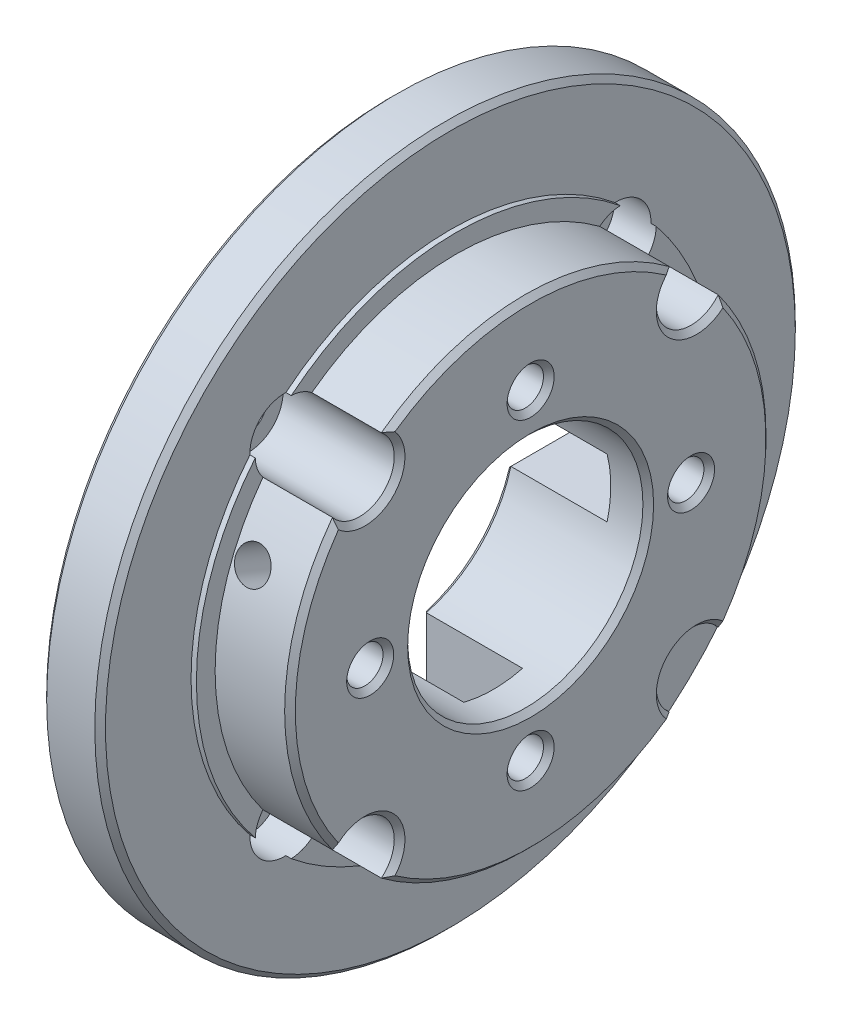
SolidWorks part; units mm, degrees
ref_plane "Ebene vorne" through (0, 0, 0) normal (0, 0, 1) x (1, 0, 0)
ref_plane "Ebene oben" through (0, 0, 0) normal (0, 1, 0) x (1, 0, 0)
ref_plane "Ebene rechts" through (0, 0, 0) normal (1, 0, 0) x (0, 0, -1)
sketch "Sketch1" plane through (0, 0, 0) normal (0, 0, 1) x (1, 0, 0)
  line L0 (0, 0) -> (49.3212, 0) construction
  line L1 (0, 0) -> (0, 32.75)
  line L2 (0, 32.75) -> (5.5, 32.75)
  line L3 (5.5, 32.75) -> (5.5, 24.25)
  line L4 (5.5, 24.25) -> (6, 24.25)
  line L5 (6, 24.25) -> (6, 22.5)
  line L6 (6, 22.5) -> (13, 22.5)
  line L7 (13, 22.5) -> (13, 0)
  line L8 (13, 11) -> (0, 11)
  dimension "D1" = 65.5
  dimension "D2" = 48.5
  dimension "D3" = 45
  dimension "D4" = 0.5
  dimension "D5" = 5.5
  dimension "D6" = 7
  dimension "D7" = 22
revolve "Revolve1" add sketch "Sketch1" angle 360 about L0
hole_wizard "M3 Clearance Hole1" positions "Sketch3" profile "Sketch5" hole size "M3" standard "DIN" end condition through all
sketch "Sketch3" plane through (13, 0, 0) normal (1, 0, 0) x (0, 0, -1)
  line L0 (0, 0) -> (0, 15) construction
  line L2 (0, 0) -> (15, 0) construction
  circle A0 centre (0, 0) radius 15
  point P4 (15, 0)
  point P29 (0, -15)
  point P30 (-15, 0)
  point P31 (0, 15)
  dimension "D1" = 30
  dimension "D2" = 90
  dimension "D3" = 4
sketch "Sketch5" plane through (13, 15, 0) normal (0, 1, 0) x (0, 0, -1)
  line L0 (0, 0) -> (0, 13)
  line L1 (0, 13) -> (1.7, 13)
  line L2 (1.7, 13) -> (1.7, 0)
  line L5 (1.7, 0) -> (0, 0)
  line L11 (0, -6.35) -> (0, 107.95) construction
  dimension "Thru Hole Dia." = 3.4
  dimension "Thru Hole Depth" = 13
sketch "Sketch6" plane through (0, 0, 0) normal (-1, 0, 0) x (0, 0, 1)
  line L0 (-2.75, 13.4123) -> (-2.75, 10.6507)
  line L7 (0, 11.8246) -> (2.75, 13.4123)
  line L8 (2.75, 13.4123) -> (2.75, 16.5877)
  line L15 (2.75, 16.5877) -> (0, 18.1754)
  line L16 (0, 18.1754) -> (-2.75, 16.5877)
  line L23 (-2.75, 16.5877) -> (-2.75, 13.4123)
  line L24 (-2.75, 13.4123) -> (0, 11.8246)
  line L31 (2.75, 13.4123) -> (2.75, 10.6507)
  line L32 (11.8246, 0) -> (13.4123, -2.75)
  line L33 (13.4123, -2.75) -> (16.5877, -2.75)
  line L34 (16.5877, -2.75) -> (18.1754, 0)
  line L35 (18.1754, 0) -> (16.5877, 2.75)
  line L36 (16.5877, 2.75) -> (13.4123, 2.75)
  line L37 (13.4123, 2.75) -> (11.8246, 0)
  line L38 (13.4123, 2.75) -> (10.6507, 2.75)
  line L39 (13.4123, -2.75) -> (10.6507, -2.75)
  line L40 (0, -11.8246) -> (-2.75, -13.4123)
  line L41 (-2.75, -13.4123) -> (-2.75, -16.5877)
  line L42 (-2.75, -16.5877) -> (0, -18.1754)
  line L43 (0, -18.1754) -> (2.75, -16.5877)
  line L44 (2.75, -16.5877) -> (2.75, -13.4123)
  line L45 (2.75, -13.4123) -> (0, -11.8246)
  line L46 (2.75, -13.4123) -> (2.75, -10.6507)
  line L47 (-2.75, -13.4123) -> (-2.75, -10.6507)
  line L48 (-11.8246, 0) -> (-13.4123, 2.75)
  line L49 (-13.4123, 2.75) -> (-16.5877, 2.75)
  line L50 (-16.5877, 2.75) -> (-18.1754, 0)
  line L51 (-18.1754, 0) -> (-16.5877, -2.75)
  line L52 (-16.5877, -2.75) -> (-13.4123, -2.75)
  line L53 (-13.4123, -2.75) -> (-11.8246, 0)
  line L54 (-13.4123, -2.75) -> (-10.6507, -2.75)
  line L55 (-13.4123, 2.75) -> (-10.6507, 2.75)
  circle A0 centre (0, 15) radius 2.75 construction
  circle A3 centre (0, 0) radius 11 construction
  point P41 (0, 0)
  dimension "D1" = 5.5
extrude "Cut-Extrude1" cut sketch "Sketch6" against normal offset from surface (9.5 mm away) 3.5
sketch "Sketch7" plane through (13, 0, 0) normal (1, 0, 0) x (0, 0, -1)
  line L1 (-15.5, -15.5) -> (15.5, -15.5)
  line L2 (-15.5, -15.5) -> (-15.5, 15.5)
  line L3 (-15.5, 15.5) -> (15.5, 15.5)
  line L4 (15.5, -15.5) -> (15.5, 15.5)
  line L5 (-15.5, -15.5) -> (15.5, 15.5) construction
  line L6 (-15.5, 15.5) -> (15.5, -15.5) construction
  circle A0 centre (0, 0) radius 21.9203
  circle A1 centre (-15.5, 15.5) radius 3.25
  circle A2 centre (-15.5, -15.5) radius 3.25
  circle A3 centre (15.5, -15.5) radius 3.25
  circle A4 centre (15.5, 15.5) radius 3.25
  dimension "D1" = 31
  dimension "D3" = 6.5
  dimension "D2" = 31
  dimension "D4" = 4
extrude "Cut-Extrude2" cut sketch "Sketch7" against normal up to surface (7.5 mm away) contours A1 | A4 | A3 | A2 up to face at (5.5, 0, 24.25)
hole_wizard "CBORE for M3 Hex Socket Head Cap Screw1" positions "Sketch8" profile "Sketch9" counterbore size "M3" standard "DIN" end condition through all
sketch "Sketch8" plane through (5.5, 0, 0) normal (1, 0, 0) x (0, 0, -1)
  point P0 (-15.5, 15.5)
  point P3 (15.5, 15.5)
  point P6 (15.5, -15.5)
  point P9 (-15.5, -15.5)
sketch "Sketch9" plane through (5.5, 15.5, 15.5) normal (0, 1, 0) x (0, 0, -1)
  line L0 (0, 0) -> (0, 5.5)
  line L1 (0, 5.5) -> (1.7, 5.5)
  line L3 (1.7, 5.5) -> (1.7, 3.4)
  line L4 (1.7, 3.4) -> (3.25, 3.4)
  line L5 (3.25, 3.4) -> (3.25, 0)
  line L7 (3.25, 0) -> (0, 0)
  line L11 (0, -6.35) -> (0, 107.95) construction
  dimension "Thru Hole Dia." = 3.4
  dimension "Thru Hole Depth" = 5.5
  dimension "C'Bore Dia." = 6.5
  dimension "C'Bore Depth" = 3.4
ref_plane "Plane1" through (0, 8.6104, 20.7873) normal (0, 0.3827, 0.9239) x (-1, 0, 0)
sketch "Sketch12" plane through (0, 8.6104, 20.7873) normal (0, 0.3827, 0.9239) x (-1, 0, 0)
  line L0 (-13, 0) -> (-7.8, 0) construction
  line L1 (-13, 19.3351) -> (-13, -5.5356) construction
  circle A0 centre (-7.8, 0) radius 1.6
  point P3 (0, 0)
  dimension "D1" = 3.2
  dimension "D2" = 5.2
extrude "Cut-Extrude3" cut sketch "Sketch12" against normal up to next
chamfer "Chamfer1" distance 0.5 angle 45 35 edges at (13, 0, 11) (13, 22.5, 0) (13, 0, -22.5) (13, -22.5, 0) (13, 0, 22.5) (13, -13.2019, 13.2019) (13, -13.2019, -13.2019) (13, 13.2019, -13.2019) (13, 13.2019, 13.2019) (13, 15, -1.7) (13, 0, 13.3) (13, -15, -1.7) (13, 0, -16.7) (0, 7.7782, -7.7782) (0, -7.7782, -7.7782) (0, -7.7782, 7.7782) (0, 13.6192, -2.75) (0, 13.6192, 2.75) (0, 17.3816, 1.375) (0, 17.3816, -1.375) (0, 2.75, 13.6192) (0, -2.75, 13.6192) (0, -1.375, 17.3816) (0, 1.375, 17.3816) (0, 7.7782, 7.7782) (0, -13.6192, -2.75) (0, -17.3816, -1.375) (0, -17.3816, 1.375) (0, -13.6192, 2.75) (0, 0, 32.75) (5.5, 0, 32.75) (0, 2.75, -13.6192) (0, 1.375, -17.3816) (0, -1.375, -17.3816) (0, -2.75, -13.6192)
